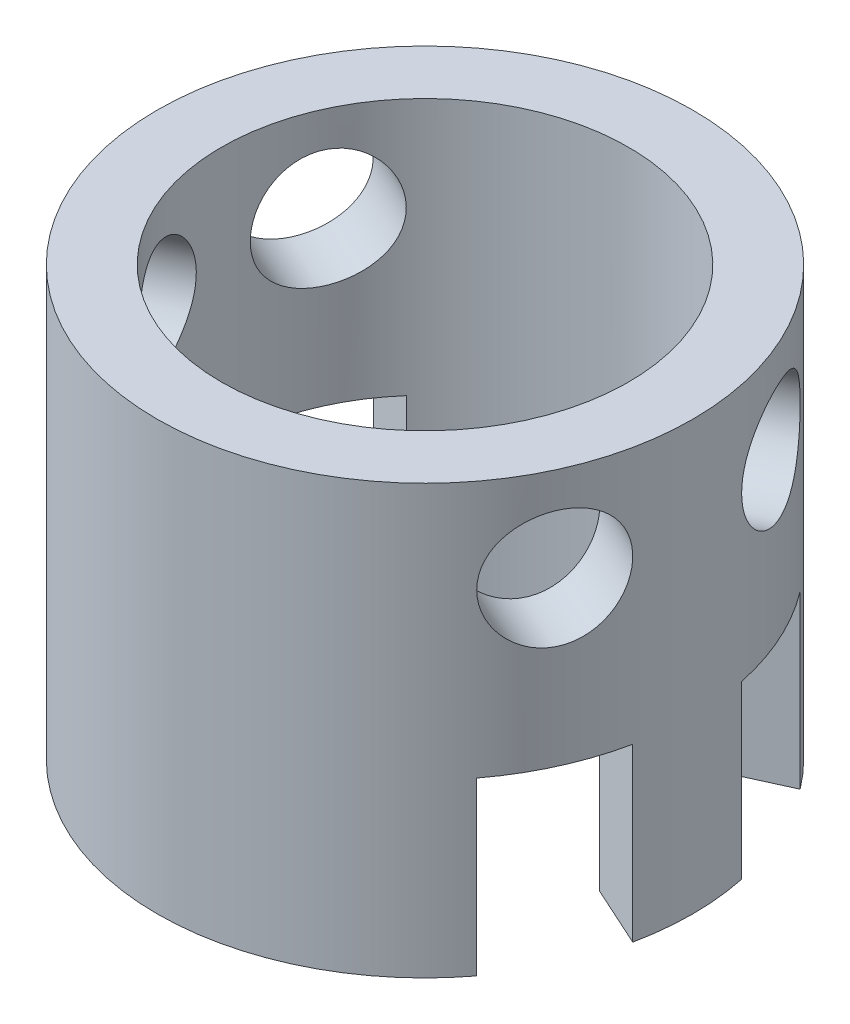
SolidWorks part; units mm, degrees
ref_plane "Front Plane" through (0, 0, 0) normal (0, 0, 1) x (1, 0, 0)
ref_plane "Top Plane" through (0, 0, 0) normal (0, 1, 0) x (1, 0, 0)
ref_plane "Right Plane" through (0, 0, 0) normal (1, 0, 0) x (0, 0, -1)
sketch "Sketch1" plane through (0, 0, 0) normal (0, 1, 0) x (1, 0, 0)
  circle A0 centre (0, 0) radius 12.5
  circle A1 centre (0, 0) radius 9.5
  dimension "D1" = 25
  dimension "D2" = 3
extrude "Boss-Extrude1" add sketch "Sketch1" along normal blind 20
ref_plane "Plane1" through (0, 3.039, 0) normal (-0.9104, 0, 0.4138) x (0.4138, 0, 0.9104)
sketch "Sketch2" plane through (0, 3.039, 0) normal (-0.9104, 0, 0.4138) x (0.4138, 0, 0.9104)
  circle A0 centre (0, 12.561) radius 2.75
  dimension "D1" = 5.5
extrude "Cut-Extrude1" cut sketch "Sketch2" against normal through all both and the other way through all
ref_plane "Plane2" through (-18.0253, 3.039, -8.1931) normal (-0.9104, 0, -0.4138) x (-0.4138, 0, 0.9104)
sketch "Sketch3" plane through (-18.0253, 3.039, -8.1931) normal (-0.9104, 0, -0.4138) x (-0.4138, 0, 0.9104)
  circle A0 centre (0, 12.561) radius 2.75
  dimension "D1" = 5.5
extrude "Cut-Extrude2" cut sketch "Sketch3" against normal through all both and the other way through all
sketch "Sketch6" plane through (0, 0, 0) normal (0, 1, 0) x (1, 0, 0)
  line L0 (-9.9629, -7.5492) -> (-7.1403, -6.2663)
  line L1 (-12.2388, -2.5422) -> (-9.4162, -1.2592)
  line L2 (-9.4162, -1.2592) -> (-12.2388, -2.5422) construction
  line L3 (-12.2388, 2.5422) -> (-9.4162, 1.2592)
  line L4 (-12.2388, 2.5422) -> (-9.4162, 1.2592) construction
  line L5 (-7.1403, 6.2663) -> (-9.9629, 7.5492)
  line L6 (-7.1403, 6.2663) -> (-9.9629, 7.5492) construction
  line L7 (7.1403, 6.2663) -> (9.9629, 7.5492)
  line L8 (9.4162, 1.2592) -> (12.2388, 2.5422)
  line L9 (9.4162, 1.2592) -> (12.2388, 2.5422) construction
  line L10 (7.1403, -6.2663) -> (9.9629, -7.5492)
  line L11 (7.1403, -6.2663) -> (9.9629, -7.5492) construction
  line L12 (9.4162, -1.2592) -> (12.2388, -2.5422)
  line L13 (12.2388, -2.5422) -> (9.4162, -1.2592) construction
  line L14 (9.9629, 7.5492) -> (7.1403, 6.2663) construction
  circle A0 centre (0, 0) radius 12.5 construction
  circle A1 centre (0, 0) radius 9.5 construction
  arc A2 (-9.9629, 7.5492) -> (-12.2388, 2.5422) centre (0, 0) ccw
  arc A3 (-7.1403, 6.2663) -> (-9.4162, 1.2592) centre (0, 0) ccw
  arc A4 (7.1403, -6.2663) -> (9.4162, -1.2592) centre (0, 0) ccw
  arc A5 (9.9629, -7.5492) -> (12.2388, -2.5422) centre (0, 0) ccw
  arc A6 (9.4162, 1.2592) -> (7.1403, 6.2663) centre (0, 0) ccw
  arc A7 (12.2388, 2.5422) -> (9.9629, 7.5492) centre (0, 0) ccw
  arc A8 (-9.4162, -1.2592) -> (-7.1403, -6.2663) centre (0, 0) ccw
  arc A9 (-12.2388, -2.5422) -> (-9.9629, -7.5492) centre (0, 0) ccw
extrude "Cut-Extrude3" cut sketch "Sketch6" along normal blind 8
